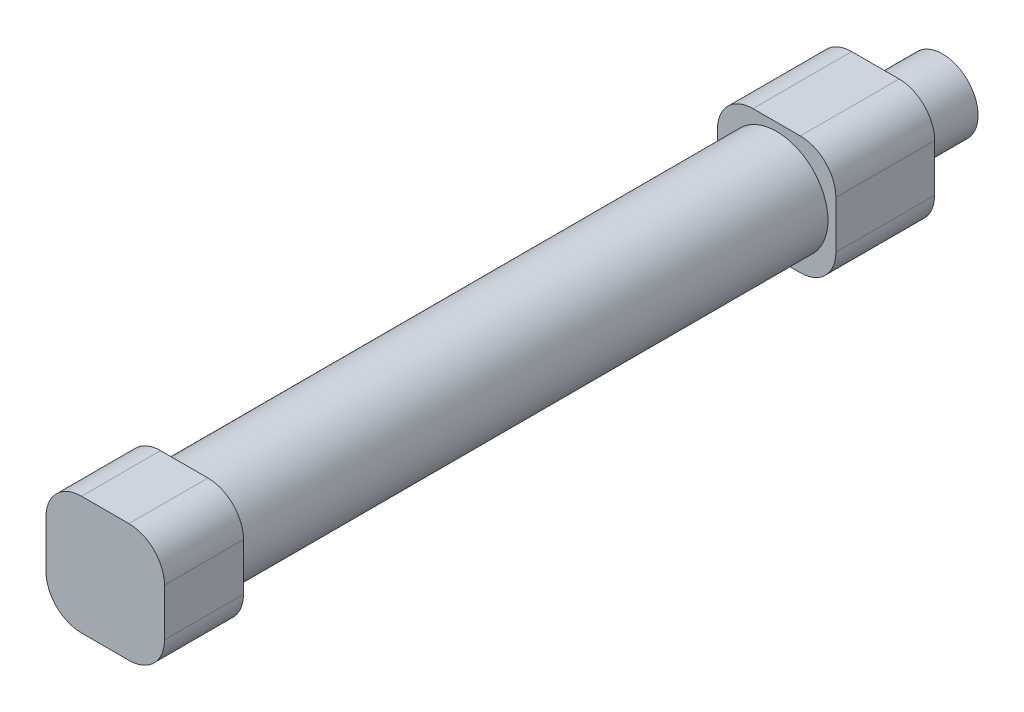
SolidWorks part; units mm, degrees
ref_plane "前视基准面" through (0, 0, 0) normal (0, 0, 1) x (1, 0, 0)
ref_plane "上视基准面" through (0, 0, 0) normal (0, 1, 0) x (1, 0, 0)
ref_plane "右视基准面" through (0, 0, 0) normal (1, 0, 0) x (0, 0, -1)
sketch "草图1" plane through (0, 0, 0) normal (0, 0, 1) x (1, 0, 0)
  line L1 (-7.5, -7.5) -> (7.5, -7.5)
  line L2 (-7.5, -7.5) -> (-7.5, 7.5)
  line L3 (-7.5, 7.5) -> (7.5, 7.5)
  line L4 (7.5, -7.5) -> (7.5, 7.5)
  line L5 (0, 7.5) -> (0, -7.5) construction
  line L6 (-7.5, 0) -> (7.5, 0) construction
  point P0 (0, 0)
  dimension "D1" = 15
  dimension "D2" = 15
extrude "凸台-拉伸1" add sketch "草图1" along normal blind 10
fillet "圆角1" radius 4.5 4 edges at (-7.5, -7.5, 5) (-7.5, 7.5, 5) (7.5, -7.5, 5) (7.5, 7.5, 5)
sketch "草图2" plane through (-7.5, 0, 0) normal (-1, 0, 0) x (0, 0, 1)
  line L0 (0, 0) -> (10, 0) construction
  line L1 (0, 3) -> (0, -3) construction
  line L2 (10, 3) -> (10, -3) construction
  line L3 (5, 3) -> (5, -3) construction
  line L4 (10, 3) -> (0, 3) construction
  line L5 (0, -3) -> (10, -3) construction
  circle A0 centre (5, 0) radius 2.5
  dimension "D1" = 5
extrude "切除-拉伸1" cut sketch "草图2" against normal blind 4.8
cosmetic thread "装饰螺纹线1" parameters "D2"=6
sketch "草图4" plane through (0, 0, 0) normal (0, 0, -1) x (-1, 0, 0)
  circle A0 centre (0, 0) radius 6.5
  dimension "D1" = 13
extrude "凸台-拉伸2" add sketch "草图4" along normal blind 75
sketch "草图6" plane through (0, 0, -75) normal (0, 0, -1) x (-1, 0, 0)
  line L1 (-7.5, -7.5) -> (7.5, -7.5)
  line L2 (-7.5, -7.5) -> (-7.5, 7.5)
  line L3 (-7.5, 7.5) -> (7.5, 7.5)
  line L4 (7.5, -7.5) -> (7.5, 7.5)
  line L5 (0, 7.5) -> (0, -7.5) construction
  line L6 (-7.5, 0) -> (7.5, 0) construction
  point P0 (0, 0)
  dimension "D1" = 15
extrude "凸台-拉伸3" add sketch "草图6" along normal blind 12.5
fillet "圆角2" radius 4.5 4 edges at (7.5, -7.5, -81.25) (-7.5, -7.5, -81.25) (-7.5, 7.5, -81.25) (7.5, 7.5, -81.25)
sketch "草图7" plane through (0, 0, -87.5) normal (0, 0, -1) x (-1, 0, 0)
  circle A0 centre (0, 0) radius 4.5
  dimension "D1" = 9
extrude "凸台-拉伸4" add sketch "草图7" along normal blind 8.5
cosmetic thread "装饰螺纹线2" parameters "D2"=8
sketch "草图13" plane through (-7.5, 0, 0) normal (-1, 0, 0) x (0, 0, 1)
  line L0 (-75, -3) -> (-75, 3) construction
  circle A0 centre (-79.5, 0) radius 2.5
  point P4 (0, 0)
  point P12 (-75, 0)
  dimension "D1" = 5
  dimension "D2" = 4.5
extrude "切除-拉伸2" cut sketch "草图13" against normal blind 4.8
cosmetic thread "装饰螺纹线3" parameters "D2"=5.1
sketch "草图16" plane through (0, 0, -96) normal (0, 0, -1) x (-1, 0, 0)
  circle A0 centre (0, 0) radius 2.5
  dimension "D1" = 5
extrude "切除-拉伸6" cut sketch "草图16" against normal blind 60
